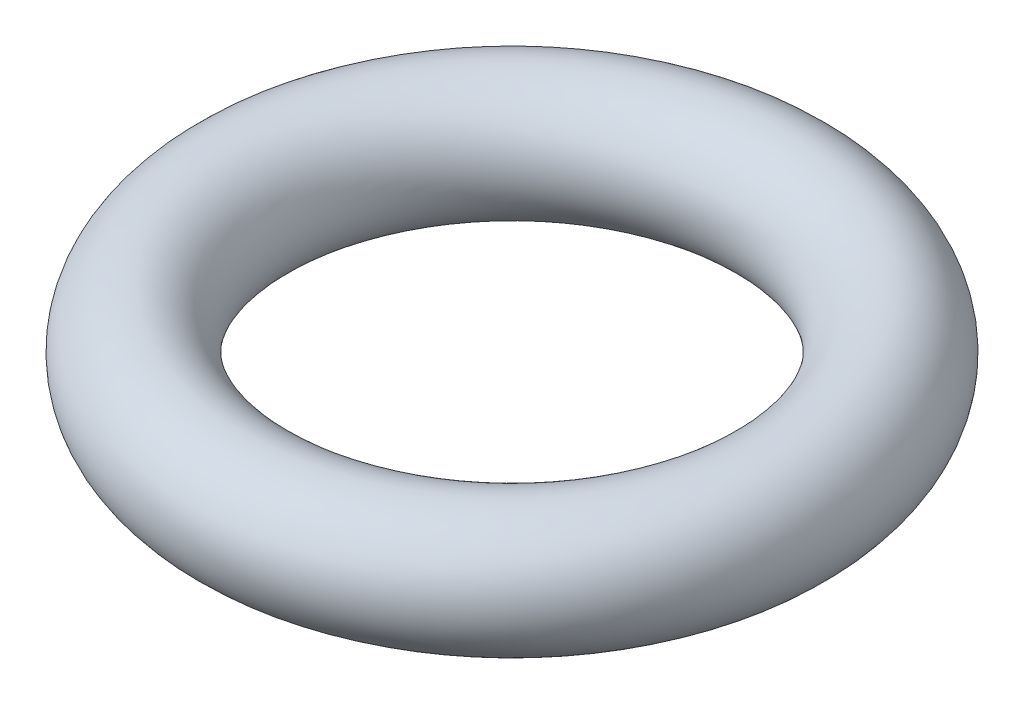
SolidWorks part; units mm, degrees
ref_plane "基准面1" through (0, 0, 0) normal (0, 0, 1) x (1, 0, 0)
ref_plane "基准面2" through (0, 0, 0) normal (0, 1, 0) x (1, 0, 0)
ref_plane "基准面3" through (0, 0, 0) normal (1, 0, 0) x (0, 0, -1)
sketch "尺寸草图" plane through (0, 0, 0) normal (0, 0, 1) x (1, 0, 0)
  point P0 (-3.3411, -3.0232)
  point P1 (2.6589, -3.0232)
  point P2 (4.4589, -3.0232)
  dimension "d1" = 6
  dimension "d2" = 1.8
sketch "草图1" plane through (0, 0, 0) normal (0, 0, 1) x (1, 0, 0)
  line L0 (0, 0) -> (0, 0.5191) construction
  circle A0 centre (3.9, 0) radius 0.9
  dimension "D1" = 1.8
  dimension "D2" = 6
revolve "基体-旋转" add sketch "草图1" angle 360 about L0
